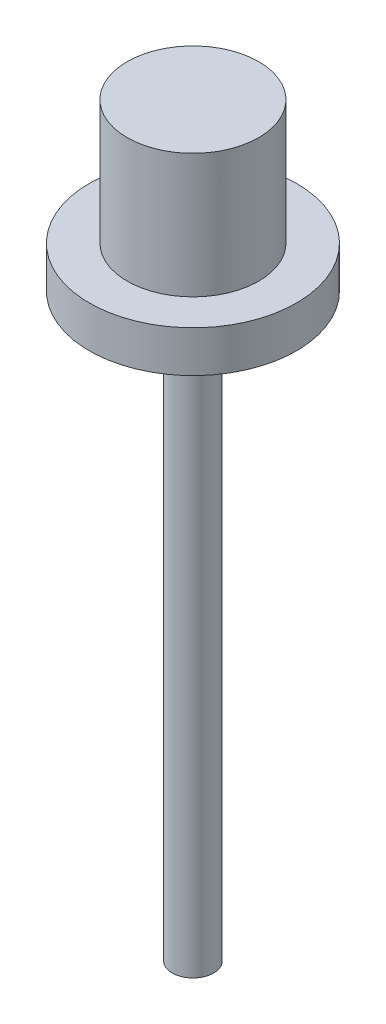
SolidWorks part; units mm, degrees
ref_plane "前视基准面" through (0, 0, 0) normal (0, 0, 1) x (1, 0, 0)
ref_plane "上视基准面" through (0, 0, 0) normal (0, 1, 0) x (1, 0, 0)
ref_plane "右视基准面" through (0, 0, 0) normal (1, 0, 0) x (0, 0, -1)
other "Configuration Table"
sketch "草图1" plane through (0, 0, 0) normal (0, 1, 0) x (1, 0, 0)
  circle A0 centre (0, 0) radius 3.175
  dimension "D1" = 6.35
extrude "凸台-拉伸1" add sketch "草图1" along normal blind 6
sketch "草图2" plane through (0, 0, 0) normal (0, -1, 0) x (-1, 0, 0)
  circle A0 centre (0, 0) radius 1
  dimension "D1" = 2
extrude "凸台-拉伸2" add sketch "草图2" along normal blind 30
sketch "草图3" plane through (0, 0, 0) normal (0, -1, 0) x (-1, 0, 0)
  circle A0 centre (0, 0) radius 5
  dimension "D1" = 10
extrude "凸台-拉伸3" add sketch "草图3" along normal blind 2
